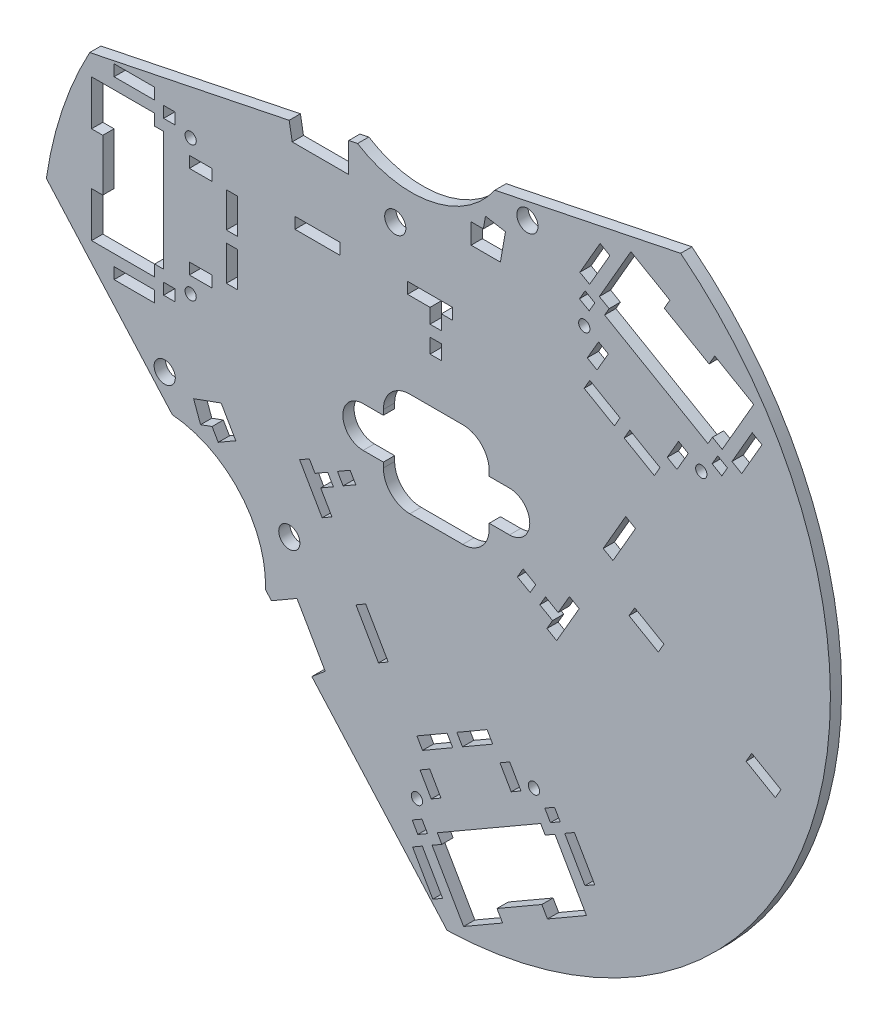
SolidWorks part; units mm, degrees
material "Balsa"
ref_plane "Plan de face" through (0, 0, 0) normal (0, 0, 1) x (1, 0, 0)
ref_plane "Plan de dessus" through (0, 0, 0) normal (0, 1, 0) x (1, 0, 0)
ref_plane "Plan de droite" through (0, 0, 0) normal (1, 0, 0) x (0, 0, -1)
sketch "Esquisse1" plane through (0, 0, 0) normal (0, 0, 1) x (1, 0, 0)
  circle A0 centre (148.0804, -12.1102) radius 175
extrude "Boss.-Extru.1" add sketch "Esquisse1" along normal blind 5
sketch "Esquisse2" plane through (0, 0, 0) normal (0, 0, -1) x (-1, 0, 0)
  line L0 (-155.3118, 53.7774) -> (-135.3118, 53.7774)
  line L1 (-150.3118, 37.2774) -> (-145.3118, 37.2774)
  line L2 (-150.3118, 37.2774) -> (-150.3118, 30.7774)
  line L3 (-150.3118, 30.7774) -> (-145.3118, 30.7774)
  line L4 (-145.3118, 37.2774) -> (-145.3118, 30.7774)
  line L5 (-105.3118, 53.7774) -> (-85.3118, 53.7774)
  line L6 (-105.3118, 53.7774) -> (-105.3118, 48.7774)
  line L7 (-105.3118, 48.7774) -> (-85.3118, 48.7774)
  line L8 (-85.3118, 53.7774) -> (-85.3118, 48.7774)
  line L9 (-59.86, 48.7774) -> (-54.86, 48.7774)
  line L10 (-59.86, 48.7774) -> (-59.86, 33.2774)
  line L11 (-59.86, 33.2774) -> (-54.86, 33.2774)
  line L12 (-54.86, 48.7774) -> (-54.86, 33.2774)
  line L13 (-59.86, 28.2774) -> (-54.86, 28.2774)
  line L14 (-59.86, 28.2774) -> (-59.86, 12.7774)
  line L15 (-59.86, 12.7774) -> (-54.86, 12.7774)
  line L16 (-54.86, 28.2774) -> (-54.86, 12.7774)
  line L17 (-48.43, 12.7774) -> (-38.43, 12.7774)
  line L18 (-48.43, 12.7774) -> (-48.43, 7.7774)
  line L19 (-48.43, 7.7774) -> (-38.43, 7.7774)
  line L20 (-38.43, 12.7774) -> (-38.43, 7.7774)
  line L21 (-32, -0.7226) -> (-27, -0.7226)
  line L22 (-32, -0.7226) -> (-32, -5.7226)
  line L23 (-32, -5.7226) -> (-27, -5.7226)
  line L24 (-27, -0.7226) -> (-27, -5.7226)
  line L25 (-23, -5.7226) -> (-5, -5.7226)
  line L26 (-23, -5.7226) -> (-23, -10.7226)
  line L27 (-23, -10.7226) -> (-5, -10.7226)
  line L28 (-5, -5.7226) -> (-5, -10.7226)
  line L29 (0, -0.7226) -> (5, -0.7226)
  line L30 (0, -0.7226) -> (0, 19.2774)
  line L31 (0, 19.2774) -> (5, 19.2774)
  line L32 (5, -0.7226) -> (5, 19.2774)
  line L33 (0, 42.2774) -> (5, 42.2774)
  line L34 (0, 42.2774) -> (0, 62.2774)
  line L35 (0, 62.2774) -> (5, 62.2774)
  line L36 (5, 42.2774) -> (5, 62.2774)
  line L37 (-23, 67.2774) -> (-5, 67.2774)
  line L38 (-23, 67.2774) -> (-23, 72.2774)
  line L39 (-23, 72.2774) -> (-5, 72.2774)
  line L40 (-5, 67.2774) -> (-5, 72.2774)
  line L41 (-27, 67.2774) -> (-32, 67.2774)
  line L42 (-27, 67.2774) -> (-27, 62.2774)
  line L43 (-27, 62.2774) -> (-32, 62.2774)
  line L44 (-32, 67.2774) -> (-32, 62.2774)
  line L45 (-38.43, 53.7774) -> (-48.43, 53.7774)
  line L46 (-38.43, 53.7774) -> (-38.43, 48.7774)
  line L47 (-38.43, 48.7774) -> (-48.43, 48.7774)
  line L48 (-48.43, 53.7774) -> (-48.43, 48.7774)
  line L49 (-135.3118, 53.7774) -> (-135.3118, 48.7774)
  line L50 (-135.3118, 48.7774) -> (-145.3118, 48.7774)
  line L51 (-135.3118, 48.7774) -> (-155.3118, 48.7774) construction
  line L52 (-145.3118, 48.7774) -> (-145.3118, 42.2774)
  line L53 (-145.3118, 42.2774) -> (-150.3118, 42.2774)
  line L54 (-150.3118, 42.2774) -> (-150.3118, 48.7774)
  line L55 (-150.3118, 48.7774) -> (-155.3118, 48.7774)
  line L56 (-155.3118, 48.7774) -> (-155.3118, 53.7774)
  line L57 (-87.4044, -38.7914) -> (-97.4044, -56.1119)
  line L58 (-104.1938, -34.8716) -> (-106.6938, -39.2017)
  line L59 (-104.1938, -34.8716) -> (-109.823, -31.6216)
  line L60 (-109.823, -31.6216) -> (-112.323, -35.9517)
  line L61 (-106.6938, -39.2017) -> (-112.323, -35.9517)
  line L62 (-112.4044, -82.0927) -> (-122.4044, -99.4132)
  line L63 (-112.4044, -82.0927) -> (-116.7345, -79.5927)
  line L64 (-116.7345, -79.5927) -> (-126.7345, -96.9132)
  line L65 (-122.4044, -99.4132) -> (-126.7345, -96.9132)
  line L66 (-139.4604, -118.9551) -> (-141.9604, -123.2852)
  line L67 (-139.4604, -118.9551) -> (-152.8838, -111.2051)
  line L68 (-152.8838, -111.2051) -> (-155.3838, -115.5352)
  line L69 (-141.9604, -123.2852) -> (-155.3838, -115.5352)
  line L70 (-157.2139, -108.7051) -> (-159.7139, -113.0352)
  line L71 (-157.2139, -108.7051) -> (-170.6373, -100.9551)
  line L72 (-170.6373, -100.9551) -> (-173.1373, -105.2852)
  line L73 (-159.7139, -113.0352) -> (-173.1373, -105.2852)
  line L74 (-176.3523, -110.8538) -> (-181.3523, -119.514)
  line L75 (-176.3523, -110.8538) -> (-180.6825, -108.3538)
  line L76 (-180.6825, -108.3538) -> (-185.6825, -117.014)
  line L77 (-181.3523, -119.514) -> (-185.6825, -117.014)
  line L78 (-196.2587, -118.3326) -> (-198.7587, -122.6627)
  line L79 (-196.2587, -118.3326) -> (-200.5888, -115.8326)
  line L80 (-200.5888, -115.8326) -> (-203.0888, -120.1627)
  line L81 (-198.7587, -122.6627) -> (-203.0888, -120.1627)
  line L82 (-205.0888, -123.6268) -> (-214.0888, -139.2153)
  line L83 (-205.0888, -123.6268) -> (-209.4189, -121.1268)
  line L84 (-209.4189, -121.1268) -> (-218.4189, -136.7153)
  line L85 (-214.0888, -139.2153) -> (-218.4189, -136.7153)
  line L86 (-212.2587, -146.0454) -> (-214.7587, -150.3755)
  line L87 (-212.2587, -146.0454) -> (-194.9382, -156.0454)
  line L88 (-194.9382, -156.0454) -> (-197.4382, -160.3755)
  line L89 (-214.7587, -150.3755) -> (-197.4382, -160.3755)
  line L90 (-175.0196, -167.5454) -> (-177.5196, -171.8755)
  line L91 (-175.0196, -167.5454) -> (-157.6991, -177.5454)
  line L92 (-157.6991, -177.5454) -> (-160.1991, -181.8755)
  line L93 (-177.5196, -171.8755) -> (-160.1991, -181.8755)
  line L94 (-141.869, -160.1268) -> (-150.869, -175.7153)
  line L95 (-141.869, -160.1268) -> (-137.5388, -162.6268)
  line L96 (-137.5388, -162.6268) -> (-146.5388, -178.2153)
  line L97 (-150.869, -175.7153) -> (-146.5388, -178.2153)
  line L98 (-139.869, -156.6627) -> (-137.369, -152.3326)
  line L99 (-139.869, -156.6627) -> (-144.1991, -154.1627)
  line L100 (-144.1991, -154.1627) -> (-141.6991, -149.8326)
  line L101 (-137.369, -152.3326) -> (-141.6991, -149.8326)
  line L102 (-145.8453, -140.014) -> (-140.8453, -131.3538)
  line L103 (-145.8453, -140.014) -> (-150.1754, -137.514)
  line L104 (-150.1754, -137.514) -> (-145.1754, -128.8538)
  line L105 (-140.8453, -131.3538) -> (-145.1754, -128.8538)
  line L106 (-97.4044, -56.1119) -> (-101.7345, -53.6119)
  line L107 (-101.7345, -53.6119) -> (-96.7345, -44.9517)
  line L108 (-96.7345, -44.9517) -> (-102.3637, -41.7017)
  line L109 (-102.3637, -41.7017) -> (-99.8637, -37.3716)
  line L110 (-99.8637, -37.3716) -> (-94.2345, -40.6216)
  line L111 (-94.2345, -40.6216) -> (-91.7345, -36.2914)
  line L112 (-91.7345, -36.2914) -> (-87.4044, -38.7914)
  line L113 (-201.5251, -51.3165) -> (-211.5251, -33.996)
  line L114 (-189.7357, -38.7364) -> (-192.2357, -34.4063)
  line L115 (-189.7357, -38.7364) -> (-184.1065, -35.4864)
  line L116 (-184.1065, -35.4864) -> (-186.6065, -31.1563)
  line L117 (-192.2357, -34.4063) -> (-186.6065, -31.1563)
  line L118 (-226.5251, -8.0153) -> (-236.5251, 9.3053)
  line L119 (-226.5251, -8.0153) -> (-222.195, -5.5153)
  line L120 (-222.195, -5.5153) -> (-232.195, 11.8053)
  line L121 (-236.5251, 9.3053) -> (-232.195, 11.8053)
  line L122 (-244.9209, 33.8472) -> (-247.4209, 38.1773)
  line L123 (-244.9209, 33.8472) -> (-231.4975, 41.5972)
  line L124 (-231.4975, 41.5972) -> (-233.9975, 45.9273)
  line L125 (-247.4209, 38.1773) -> (-233.9975, 45.9273)
  line L126 (-227.1673, 44.0972) -> (-229.6673, 48.4273)
  line L127 (-227.1673, 44.0972) -> (-213.7439, 51.8472)
  line L128 (-213.7439, 51.8472) -> (-216.2439, 56.1773)
  line L129 (-229.6673, 48.4273) -> (-216.2439, 56.1773)
  line L130 (-219.4589, 61.7458) -> (-224.4589, 70.4061)
  line L131 (-219.4589, 61.7458) -> (-215.1288, 64.2458)
  line L132 (-215.1288, 64.2458) -> (-220.1288, 72.9061)
  line L133 (-224.4589, 70.4061) -> (-220.1288, 72.9061)
  line L134 (-215.9826, 82.7246) -> (-218.4826, 87.0547)
  line L135 (-215.9826, 82.7246) -> (-211.6525, 85.2246)
  line L136 (-211.6525, 85.2246) -> (-214.1525, 89.5547)
  line L137 (-218.4826, 87.0547) -> (-214.1525, 89.5547)
  line L138 (-216.1525, 93.0188) -> (-225.1525, 108.6073)
  line L139 (-216.1525, 93.0188) -> (-211.8223, 95.5188)
  line L140 (-211.8223, 95.5188) -> (-220.8223, 111.1073)
  line L141 (-225.1525, 108.6073) -> (-220.8223, 111.1073)
  line L142 (-231.9826, 110.4374) -> (-234.4826, 114.7676)
  line L143 (-231.9826, 110.4374) -> (-249.3031, 100.4374)
  line L144 (-249.3031, 100.4374) -> (-251.8031, 104.7676)
  line L145 (-234.4826, 114.7676) -> (-251.8031, 104.7676)
  line L146 (-269.2217, 88.9374) -> (-271.7217, 93.2676)
  line L147 (-269.2217, 88.9374) -> (-286.5422, 78.9374)
  line L148 (-286.5422, 78.9374) -> (-289.0422, 83.2676)
  line L149 (-271.7217, 93.2676) -> (-289.0422, 83.2676)
  line L150 (-279.3723, 56.5188) -> (-288.3723, 72.1073)
  line L151 (-279.3723, 56.5188) -> (-283.7025, 54.0188)
  line L152 (-283.7025, 54.0188) -> (-292.7025, 69.6073)
  line L153 (-288.3723, 72.1073) -> (-292.7025, 69.6073)
  line L154 (-277.3723, 53.0547) -> (-274.8723, 48.7246)
  line L155 (-277.3723, 53.0547) -> (-273.0422, 55.5547)
  line L156 (-273.0422, 55.5547) -> (-270.5422, 51.2246)
  line L157 (-274.8723, 48.7246) -> (-270.5422, 51.2246)
  line L158 (-259.966, 49.9061) -> (-254.966, 41.2458)
  line L159 (-259.966, 49.9061) -> (-255.6359, 52.4061)
  line L160 (-255.6359, 52.4061) -> (-250.6359, 43.7458)
  line L161 (-254.966, 41.2458) -> (-250.6359, 43.7458)
  line L162 (-211.5251, -33.996) -> (-207.195, -31.496)
  line L163 (-207.195, -31.496) -> (-202.195, -40.1563)
  line L164 (-202.195, -40.1563) -> (-196.5658, -36.9063)
  line L165 (-196.5658, -36.9063) -> (-194.0658, -41.2364)
  line L166 (-194.0658, -41.2364) -> (-199.695, -44.4864)
  line L167 (-199.695, -44.4864) -> (-197.195, -48.8165)
  line L168 (-197.195, -48.8165) -> (-201.5251, -51.3165)
  point P204 (-148.0804, -12.1102)
  dimension "D1" = 3
extrude "Enlèv. mat.-Extru.1" cut sketch "Esquisse2" against normal blind 5
sketch "Esquisse3" plane through (0, 0, 0) normal (0, 0, -1) x (-1, 0, 0)
  line L0 (-59.86, 33.2774) -> (-59.86, 28.2774) construction
  line L1 (-59.86, 30.7774) -> (32.4397, 30.7774) construction
  line L2 (0, -0.7226) -> (-23, -0.7226)
  line L3 (-23, -0.7226) -> (-23, 4.2774)
  line L4 (-23, 4.2774) -> (-27, 4.2774)
  line L5 (-23, 57.2774) -> (-27, 57.2774)
  line L6 (-23, 62.2774) -> (-23, 57.2774)
  line L7 (0, 62.2774) -> (-23, 62.2774)
  line L8 (-27, 57.2774) -> (-27, 4.2774)
  line L9 (0, -0.7226) -> (0, 62.2774)
  line L10 (-212.2587, -146.0454) -> (-200.7587, -126.1268)
  line L11 (-200.7587, -126.1268) -> (-196.4286, -128.6268)
  line L12 (-196.4286, -128.6268) -> (-194.4286, -125.1627)
  line L13 (-150.5292, -155.1268) -> (-148.5292, -151.6627)
  line L14 (-146.1991, -157.6268) -> (-150.5292, -155.1268)
  line L15 (-157.6991, -177.5454) -> (-146.1991, -157.6268)
  line L16 (-148.5292, -151.6627) -> (-194.4286, -125.1627)
  line L17 (-212.2587, -146.0454) -> (-157.6991, -177.5454)
  line L18 (-152.8838, -111.2051) -> (-157.2139, -108.7051) construction
  line L19 (-155.0489, -109.9551) -> (-201.1987, -189.889) construction
  line L20 (-231.9826, 110.4374) -> (-220.4826, 90.5188)
  line L21 (-220.4826, 90.5188) -> (-224.8127, 88.0188)
  line L22 (-224.8127, 88.0188) -> (-222.8127, 84.5547)
  line L23 (-270.7121, 61.5188) -> (-268.7121, 58.0547)
  line L24 (-275.0422, 59.0188) -> (-270.7121, 61.5188)
  line L25 (-286.5422, 78.9374) -> (-275.0422, 59.0188)
  line L26 (-268.7121, 58.0547) -> (-222.8127, 84.5547)
  line L27 (-231.9826, 110.4374) -> (-286.5422, 78.9374)
  line L28 (-231.4975, 41.5972) -> (-227.1673, 44.0972) construction
  line L29 (-229.3324, 42.8472) -> (-275.4822, 122.781) construction
  point P42 (-148.0804, -12.1102)
  dimension "D1" = 5
  dimension "D2" = 4
  dimension "D3" = 23
  dimension "D4" = 3
extrude "Enlèv. mat.-Extru.2" cut sketch "Esquisse3" against normal blind 5
sketch "Esquisse4" plane through (0, 0, 0) normal (0, 0, -1) x (-1, 0, 0)
  line L0 (-32, 67.2774) -> (-32, 62.2774) construction
  line L1 (-38.43, 53.7774) -> (-48.43, 53.7774) construction
  line L2 (-27, 30.7774) -> (-93.5454, 30.7774) construction
  line L3 (-27, 57.2774) -> (-27, 4.2774) construction
  line L4 (-171.4789, -138.4127) -> (-138.2062, -80.7827) construction
  line L5 (-245.7624, 71.3047) -> (-212.4897, 13.6748) construction
  circle A0 centre (-39, 60.7774) radius 2.5
  circle A1 centre (-39, 0.7774) radius 2.5
  circle A2 centre (-139.4981, -143.0204) radius 2.5
  circle A3 centre (-191.4596, -113.0204) radius 2.5
  circle A4 centre (-265.7432, 45.9124) radius 2.5
  circle A5 centre (-213.7816, 75.9124) radius 2.5
  point P27 (-148.0804, -12.1102)
  dimension "D1" = 7
  dimension "D2" = 7
  dimension "D3" = 3
extrude "Enlèv. mat.-Extru.3" cut sketch "Esquisse4" against normal blind 5
sketch "Esquisse5" plane through (0, 0, 0) normal (0, 0, -1) x (-1, 0, 0)
  line L0 (9.513, 70.4436) -> (-93.4749, 91.6327)
  line L1 (-315.6991, 137.3538) -> (-290.787, 258.4375)
  line L2 (-290.787, 258.4375) -> (34.4251, 191.5273)
  line L3 (34.4251, 191.5273) -> (9.513, 70.4436)
  line L4 (-233.6714, -25.6375) -> (-246.6617, -33.1375)
  line L5 (-179.3609, 109.3031) -> (-315.6991, 137.3538)
  line L6 (-94.86, 83.7774) -> (-174.86, 83.7774)
  line L7 (-174.86, 83.7774) -> (-179.3609, 109.3031)
  line L8 (-233.6714, -25.6375) -> (-236.1714, -21.3074)
  line L9 (-93.4749, 91.6327) -> (-94.86, 83.7774)
  line L10 (-155.3834, -189.8669) -> (-85.5392, -111.2714)
  line L11 (65.1685, 58.3199) -> (157.574, -23.7965)
  line L12 (26.9196, -12.1102) -> (-148.0804, -12.1102) construction
  line L13 (157.574, -23.7965) -> (-62.9779, -271.9834)
  line L14 (-62.9779, -271.9834) -> (-155.3834, -189.8669)
  line L15 (-246.6617, -33.1375) -> (-249.1617, -28.8074)
  line L16 (-27.2932, -45.7272) -> (65.1685, 58.3199)
  line L17 (-91.6495, -106.1442) -> (-51.6495, -36.8622)
  line L18 (-51.6495, -36.8622) -> (-27.2932, -45.7272)
  line L19 (-236.1714, -21.3074) -> (-249.1617, -28.8074)
  line L20 (-85.5392, -111.2714) -> (-91.6495, -106.1442)
  line L21 (-148.0804, -12.1102) -> (-235.5804, -163.6646) construction
  line L22 (-93.4749, 91.6327) -> (-179.3609, 109.3031) construction
  line L23 (-139.86, 83.7774) -> (-139.86, 101.1761) construction
  line L24 (-285.6329, -55.6375) -> (-298.6233, -63.1375)
  line L25 (-285.6329, -55.6375) -> (-288.1329, -51.3074)
  line L26 (-298.6233, -63.1375) -> (-301.1233, -58.8074)
  line L27 (-288.1329, -51.3074) -> (-301.1233, -58.8074)
  line L28 (-211.5251, -33.996) -> (-201.5251, -51.3165) construction
  line L29 (-283.7025, 54.0188) -> (-279.3723, 56.5188) construction
  circle A0 centre (-188.5408, 103.7774) radius 4.7
  circle A1 centre (-129.86, 73.7774) radius 4.7
  circle A2 centre (-27.4886, -35.0143) radius 4.7
  circle A3 centre (-82.8098, -70.8333) radius 4.7
  point P15 (-148.0804, -12.1102)
  point P35 (-148.0804, -12.1102)
  dimension "D2" = 9.4
  dimension "D3" = 9.4
  dimension "D4" = 100
  dimension "D5" = 100
  dimension "D6" = 5
  dimension "D7" = 45
  dimension "D8" = 15
  dimension "D9" = 80
  dimension "D10" = 35
  dimension "D11" = 85.8876
  dimension "D12" = 58.6808
  dimension "D13" = 30
  dimension "D14" = 10
  dimension "D15" = 11.626
  dimension "D16" = 18.2204
  dimension "D18" = 17.3986
  dimension "D19" = 15
  dimension "D20" = 45
  dimension "D21" = 15
  dimension "D22" = 89
  dimension "D17" = 2
extrude "Enlèv. mat.-Extru.4" cut sketch "Esquisse5" against normal blind 5
sketch "Esquisse6" plane through (0, 0, 0) normal (0, 0, -1) x (-1, 0, 0)
  line L7 (-72.2193, -96.2825) -> (-85.5392, -111.2714)
  line L8 (-85.5392, -111.2714) -> (-94.4781, -107.3647)
  line L9 (-94.4781, -107.3647) -> (-52.0208, -31.4132)
  line L10 (-52.0208, -31.4132) -> (-27.2932, -45.7272)
  line L11 (-27.2932, -45.7272) -> (-30.866, -49.7477)
  line L13 (-113.1156, 95.6736) -> (-93.4749, 91.6327)
  line L14 (-93.4749, 91.6327) -> (-92.3887, 81.938)
  line L15 (-92.3887, 81.938) -> (-179.3934, 80.7314)
  line L16 (-179.3934, 80.7314) -> (-179.3609, 109.3031)
  line L17 (-179.3609, 109.3031) -> (-174.0926, 108.2192)
  arc A0 (-72.2193, -96.2825) -> (-30.866, -49.7477) centre (-27.2507, -94.6022) cw
  arc A2 (-113.1156, 95.6736) -> (-174.0926, 108.2192) centre (-137.0551, 133.7774) cw
  point P3 (-148.0804, -12.1102)
  point P21 (-148.0804, -12.1102)
  dimension "D1" = 45
  dimension "D2" = 2
extrude "Boss.-Extru.2" add sketch "Esquisse6" against normal blind 5
sketch "Esquisse7" plane through (0, 0, 0) normal (0, 0, -1) x (-1, 0, 0)
  line L0 (-109.1977, 94.8675) -> (-109.1977, 81.7774)
  line L1 (-113.1156, 95.6736) -> (5.8145, 71.2045) construction
  line L2 (-109.1977, 81.7774) -> (-84.1003, 81.7774)
  line L3 (-84.1003, 81.7774) -> (-82.7516, 89.4264)
  line L4 (-82.7516, 89.4264) -> (-109.1977, 94.8675)
  line L5 (26.9196, -12.1102) -> (-148.0804, -12.1102) construction
  line L6 (-74.8764, -99.2725) -> (-86.2127, -92.7274)
  line L7 (-163.5382, 81.7774) -> (-176.5382, 81.7774)
  line L8 (-176.5382, 81.7774) -> (-178.7956, 94.5799)
  line L9 (-178.7956, 94.5799) -> (-169.9324, 96.1428)
  line L10 (-169.9324, 96.1428) -> (-168.9863, 90.7774)
  line L12 (-168.9863, 90.7774) -> (-163.5382, 90.7774)
  line L13 (-163.5382, 90.7774) -> (-163.5382, 81.7774)
  line L14 (-86.2127, -92.7274) -> (-98.7614, -114.4624)
  line L15 (-98.7614, -114.4624) -> (-92.8116, -119.4549)
  line L16 (-92.8116, -119.4549) -> (-74.8764, -99.2725)
  line L17 (-59.0425, -45.6672) -> (-52.5425, -34.4088)
  line L18 (-52.5425, -34.4088) -> (-40.3265, -38.8551)
  line L19 (-40.3265, -38.8551) -> (-43.4047, -47.3123)
  line L20 (-43.4047, -47.3123) -> (-48.5242, -45.449)
  line L21 (-48.5242, -45.449) -> (-51.2483, -50.1672)
  line L22 (-51.2483, -50.1672) -> (-59.0425, -45.6672)
  point P14 (-148.0804, -12.1102)
  point P31 (-148.0804, -12.1102)
  dimension "D1" = 80
  dimension "D2" = 13.0901
  dimension "D3" = 4
  dimension "D4" = 27
  dimension "D5" = 20
  dimension "D6" = 9
  dimension "D7" = 9
  dimension "D8" = 7
  dimension "D9" = 13
  dimension "D10" = 13
  dimension "D11" = 2
extrude "Enlèv. mat.-Extru.5" cut sketch "Esquisse7" against normal blind 5
sketch "Esquisse9" plane through (0, 0, 5) normal (0, 0, 1) x (1, 0, 0)
  line L0 (171.5804, 10.8898) -> (124.5804, 10.8898) construction
  line L1 (171.5804, 10.8898) -> (171.5804, -35.1102) construction
  line L2 (124.5804, 10.8898) -> (124.5804, -35.1102) construction
  line L3 (171.5804, -35.1102) -> (124.5804, -35.1102) construction
  line L4 (145.3118, 48.7774) -> (135.3118, 48.7774) construction
  line L5 (171.5804, 10.8898) -> (124.5804, -35.1102) construction
  line L6 (124.5804, 10.8898) -> (171.5804, -35.1102) construction
  line L7 (180.5804, -12.1102) -> (115.5804, -12.1102) construction
  line L8 (180.5804, -21.1102) -> (171.5804, -21.1102)
  line L9 (180.5804, -3.1102) -> (171.5804, -3.1102)
  line L10 (159.8304, 10.8898) -> (136.3304, 10.8898)
  line L11 (124.5804, -0.8602) -> (124.5804, -3.1102)
  line L12 (124.5804, -23.3602) -> (124.5804, -21.1102)
  line L13 (159.8304, -35.1102) -> (136.3304, -35.1102)
  line L14 (171.5804, -0.8602) -> (171.5804, -3.1102)
  line L15 (171.5804, -23.3602) -> (171.5804, -21.1102)
  line L16 (124.5804, -3.1102) -> (115.5804, -3.1102)
  line L17 (124.5804, -21.1102) -> (115.5804, -21.1102)
  arc A0 (171.5804, -0.8602) -> (159.8304, 10.8898) centre (159.8304, -0.8602) ccw
  arc A1 (159.8304, -35.1102) -> (171.5804, -23.3602) centre (159.8304, -23.3602) ccw
  arc A2 (124.5804, -23.3602) -> (136.3304, -35.1102) centre (136.3304, -23.3602) ccw
  arc A3 (136.3304, 10.8898) -> (124.5804, -0.8602) centre (136.3304, -0.8602) ccw
  arc A5 (180.5804, -21.1102) -> (180.5804, -3.1102) centre (180.5804, -12.1102) ccw
  arc A6 (115.5804, -3.1102) -> (115.5804, -21.1102) centre (115.5804, -12.1102) ccw
  point P4 (148.0804, -12.1102)
  point P14 (148.0804, -12.1102)
  dimension "D1" = 47
  dimension "D2" = 46
  dimension "D3" = 11.75
  dimension "D4" = 9
  dimension "D5" = 65
  dimension "D6" = 32.5
extrude "Enlèv. mat.-Extru.6" cut sketch "Esquisse9" against normal blind 10
